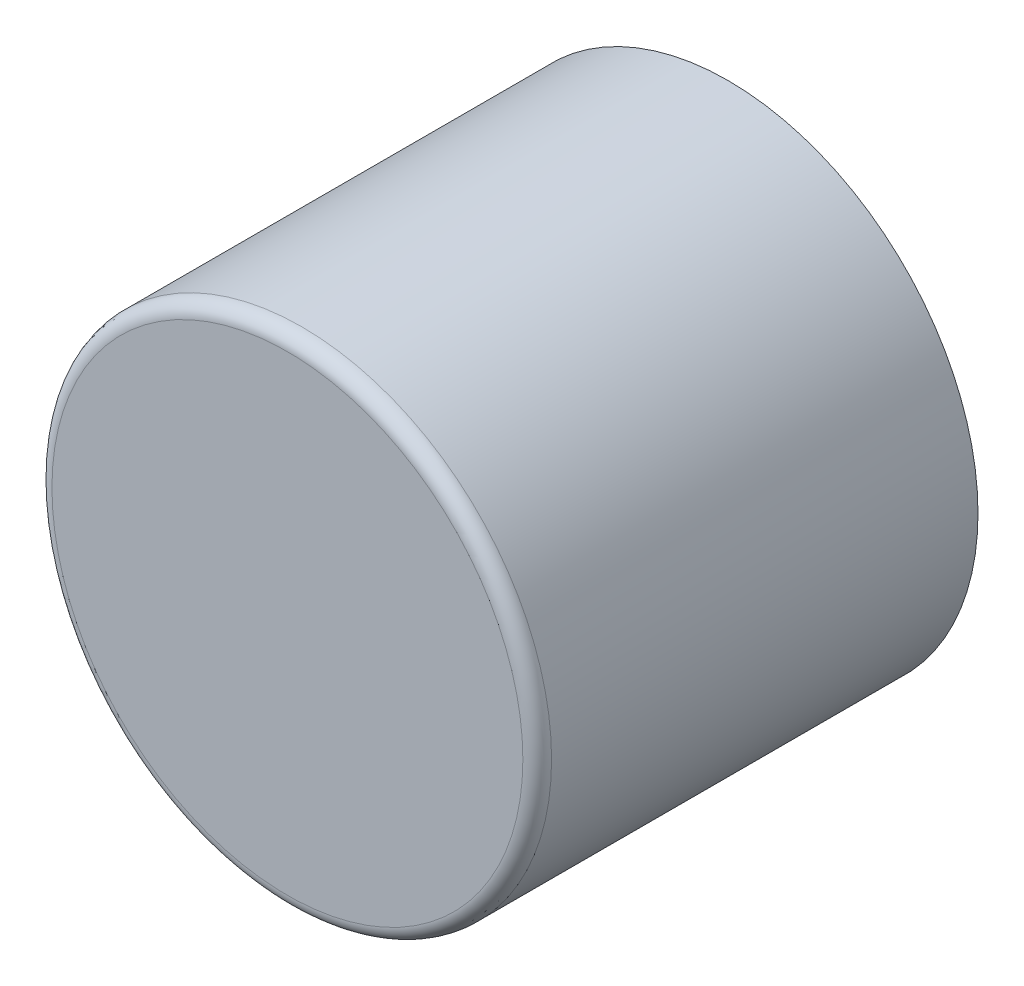
SolidWorks part; units mm, degrees
material "1.6571 (20NiCrMoS6-4)"
ref_plane "Alzado" through (0, 0, 0) normal (0, 0, 1) x (1, 0, 0)
ref_plane "Planta" through (0, 0, 0) normal (0, 1, 0) x (1, 0, 0)
ref_plane "Vista lateral" through (0, 0, 0) normal (1, 0, 0) x (0, 0, -1)
sketch "Croquis1" plane through (0, 0, 0) normal (0, 0, 1) x (1, 0, 0)
  circle A0 centre (0, 0) radius 17.4
  dimension "D1" = 34.8
extrude "Saliente-Extruir1" add sketch "Croquis1" along normal blind 30.7
fillet "Redondeo1" radius 1 1 edges at (17.4, 0, 30.7)
